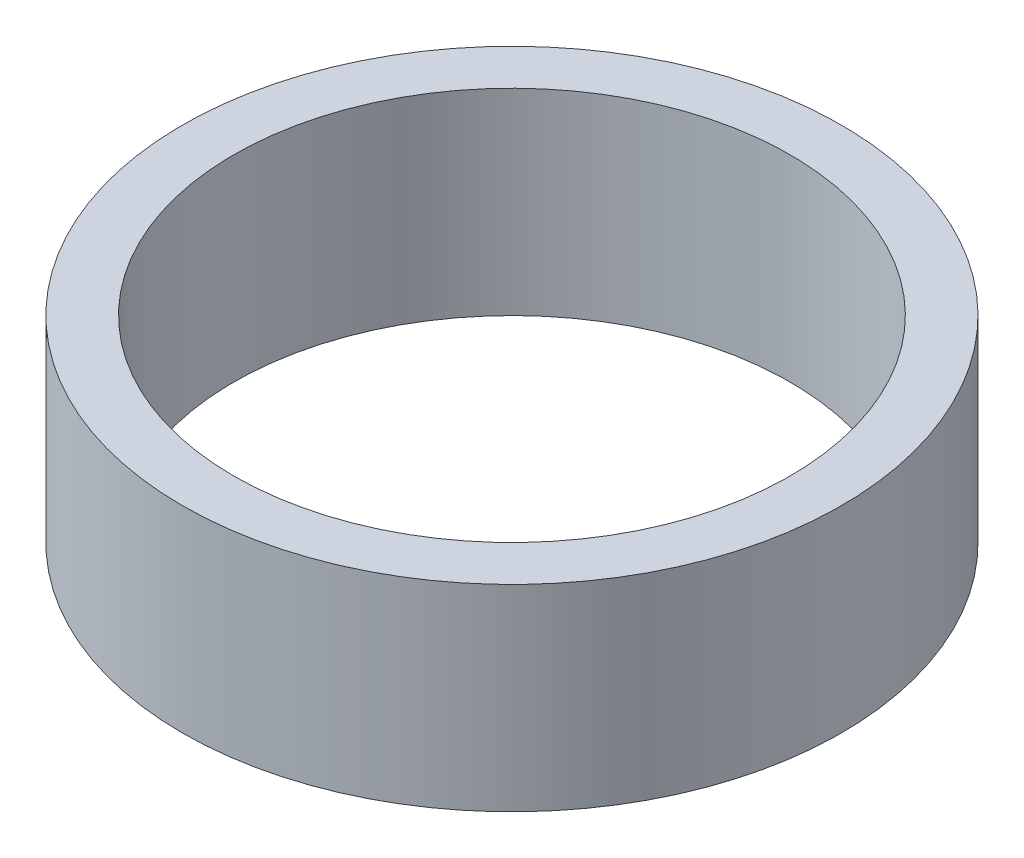
SolidWorks part; units mm, degrees
ref_plane "Plan de face" through (0, 0, 0) normal (0, 0, 1) x (1, 0, 0)
ref_plane "Plan de dessus" through (0, 0, 0) normal (0, 1, 0) x (1, 0, 0)
ref_plane "Plan de droite" through (0, 0, 0) normal (1, 0, 0) x (0, 0, -1)
sketch "Esquisse1" plane through (0, 0, 0) normal (0, 1, 0) x (1, 0, 0)
  circle A0 centre (0, 0) radius 3.85
  circle A1 centre (0, 0) radius 3.25
  dimension "D1" = 7.7
  dimension "D2" = 6.5
extrude "Boss.-Extru.1" add sketch "Esquisse1" along normal blind 2.3 contours A0 | A1
